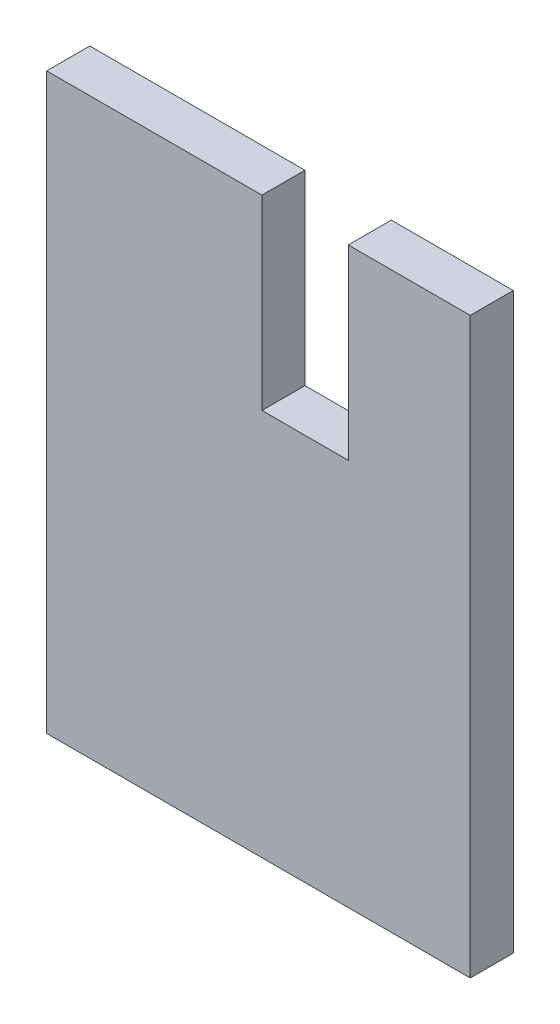
SolidWorks part; units mm, degrees
ref_plane "Front Plane" through (0, 0, 0) normal (0, 0, 1) x (1, 0, 0)
ref_plane "Top Plane" through (0, 0, 0) normal (0, 1, 0) x (1, 0, 0)
ref_plane "Right Plane" through (0, 0, 0) normal (1, 0, 0) x (0, 0, -1)
sketch "Sketch1" plane through (0, 0, 0) normal (0, 0, 1) x (1, 0, 0)
  line L0 (0, 0) -> (0, 80)
  line L1 (0, 80) -> (30, 80)
  line L2 (30, 80) -> (30, 54)
  line L3 (30, 54) -> (42.04, 54)
  line L4 (42.04, 54) -> (42.04, 80)
  line L5 (42.04, 80) -> (59.04, 80)
  line L6 (59.04, 80) -> (59.04, 0)
  line L7 (59.04, 0) -> (0, 0)
  dimension "D1" = 80
  dimension "D3" = 12.04
  dimension "D4" = 26
  dimension "D5" = 26
  dimension "D6" = 17
extrude "Boss-Extrude1" add sketch "Sketch1" along normal blind 6
